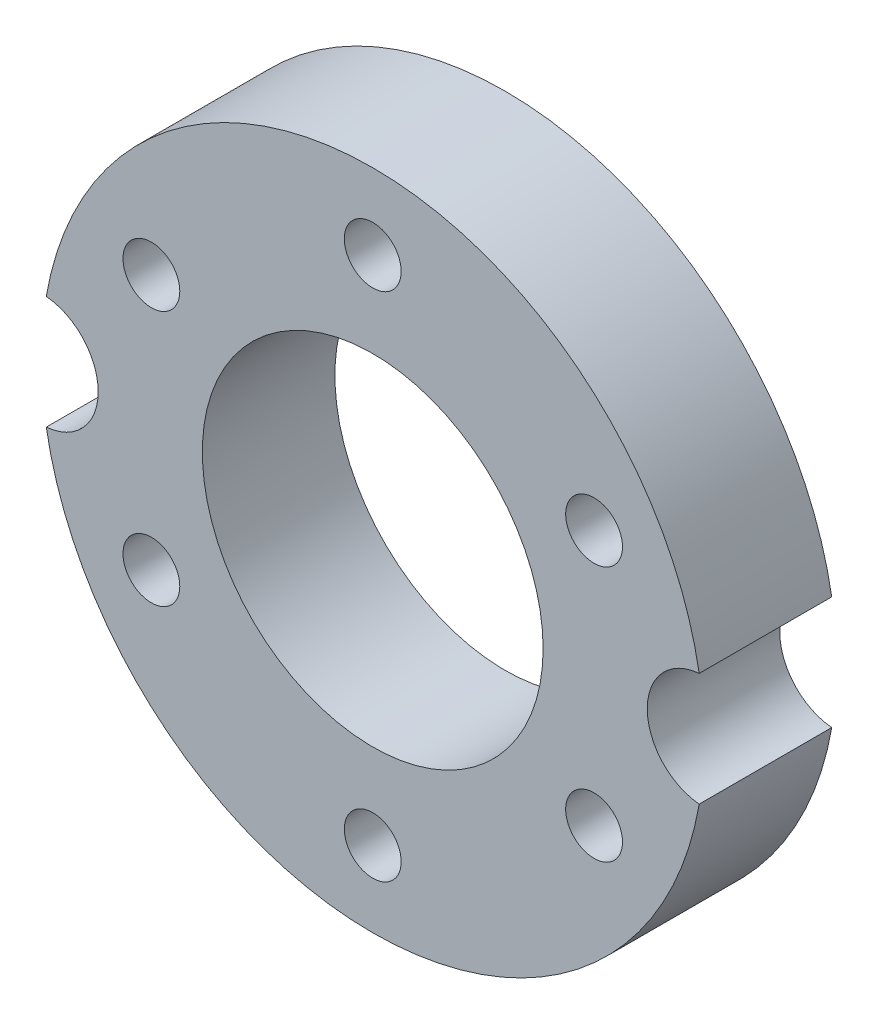
SolidWorks part; units mm, degrees
ref_plane "前视基准面" through (0, 0, 0) normal (0, 0, 1) x (1, 0, 0)
ref_plane "上视基准面" through (0, 0, 0) normal (0, 1, 0) x (1, 0, 0)
ref_plane "右视基准面" through (0, 0, 0) normal (1, 0, 0) x (0, 0, -1)
other "Configuration Table"
sketch "草图1" plane through (0, 0, 0) normal (0, 0, 1) x (1, 0, 0)
  line L0 (0, 9) -> (0, -9) construction
  circle A0 centre (0, 0) radius 13.5 construction
  circle A1 centre (0, 13.5) radius 1.5
  circle A2 centre (11.6913, 6.75) radius 1.5
  circle A3 centre (11.6913, -6.75) radius 1.5
  circle A4 centre (0, -13.5) radius 1.5
  circle A5 centre (-11.6913, -6.75) radius 1.5
  circle A6 centre (-11.6913, 6.75) radius 1.5
  circle A7 centre (0, 0) radius 17.5
  circle A8 centre (0, 0) radius 9
  arc A9 (-17.2429, 2.989) -> (-17.2429, -2.989) centre (-17.5, 0) cw
  arc A10 (17.2429, 2.989) -> (17.2429, -2.989) centre (17.5, 0) ccw
  point P17 (0, 0)
  dimension "D1" = 27
  dimension "D2" = 3
  dimension "D4" = 35
  dimension "D5" = 18
  dimension "D6" = 3
  dimension "D3" = 6
extrude "凸台-拉伸1" add sketch "草图1" along normal blind 7 contours A10 A7 A9 A8 A1 A2 A3 A4 A5 A6
